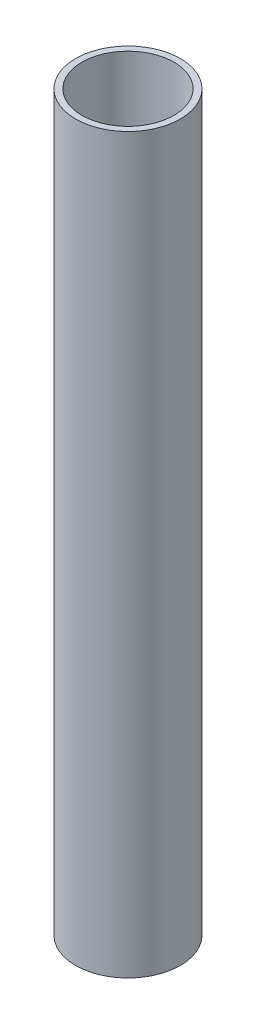
SolidWorks part; units mm, degrees
material "Thornel Mat VMA"
ref_plane "前视基准面" through (0, 0, 0) normal (0, 0, 1) x (1, 0, 0)
ref_plane "上视基准面" through (0, 0, 0) normal (0, 1, 0) x (1, 0, 0)
ref_plane "右视基准面" through (0, 0, 0) normal (1, 0, 0) x (0, 0, -1)
sketch "草图1" plane through (0, 0, 0) normal (0, 1, 0) x (1, 0, 0)
  circle A0 centre (0, 0) radius 11
  circle A1 centre (0, 0) radius 12.5
  dimension "D1" = 25
  dimension "D2" = 22
extrude "凸台-拉伸1" add sketch "草图1" along normal blind 175
